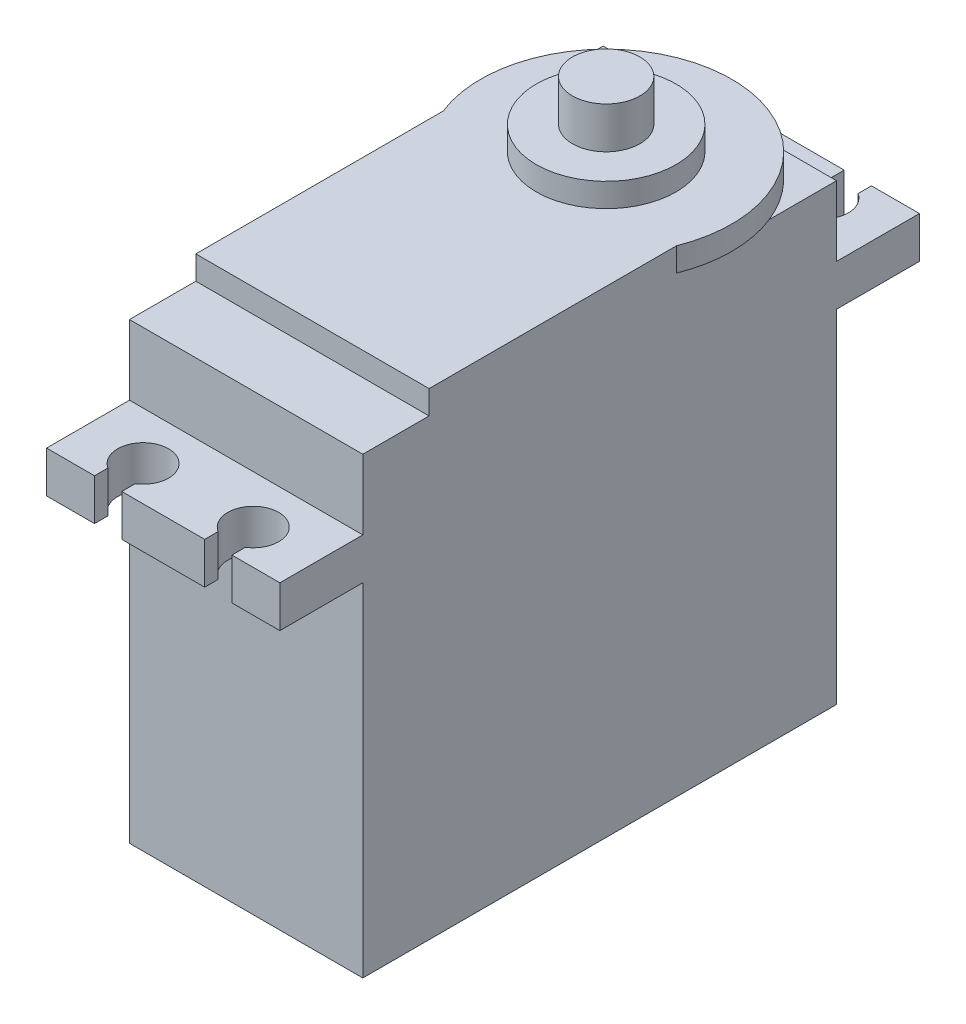
SolidWorks part; units mm, degrees
material "Nailon 101"
ref_plane "Front" through (0, 0, 0) normal (0, 0, 1) x (1, 0, 0)
ref_plane "Top" through (0, 0, 0) normal (0, 1, 0) x (1, 0, 0)
ref_plane "Right" through (0, 0, 0) normal (1, 0, 0) x (0, 0, -1)
sketch "Croquis1" plane through (0, 0, 0) normal (1, 0, 0) x (0, 0, -1)
  line L1 (0, 0) -> (40, 0)
  line L2 (0, 0) -> (0, 38.3)
  line L3 (0, 38.3) -> (40, 38.3)
  line L4 (40, 0) -> (40, 38.3)
  dimension "D1" = 40
  dimension "D2" = 38.3
extrude "Saliente-Extruir1" add sketch "Croquis1" along normal blind 19.7
sketch "Croquis2" plane through (0, 38.3, 0) normal (0, 1, 0) x (1, 0, 0)
  line L0 (0, 40) -> (0, 0) construction
  line L1 (0, 5.6) -> (19.7, 5.6)
  line L2 (0, 5.6) -> (0, 26.4837)
  line L4 (19.7, 5.6) -> (19.7, 26.4837)
  line L6 (19.7, 0) -> (0, 0) construction
  arc A0 (19.7, 26.4837) -> (0, 26.4837) centre (9.85, 30.4) ccw
  point P8 (9.85, 5.6)
  dimension "D3" = 21.2
  dimension "D1" = 5.6
  dimension "D2" = 9.85
  dimension "D4" = 9.85
  dimension "D5" = 26.4837
extrude "Saliente-Extruir2" add sketch "Croquis2" along normal blind 2
sketch "Croquis3" plane through (0, 40.3, 0) normal (0, 1, 0) x (1, 0, 0)
  circle A0 centre (9.85, 30.4) radius 5.9
  arc A1 (19.7, 26.4837) -> (0, 26.4837) centre (9.85, 30.4) ccw construction
  dimension "D1" = 11.8
extrude "Saliente-Extruir3" add sketch "Croquis3" along normal blind 2
sketch "Croquis4" plane through (0, 42.3, 0) normal (0, 1, 0) x (1, 0, 0)
  circle A0 centre (9.85, 30.4) radius 2.85
  circle A1 centre (9.85, 30.4) radius 5.9 construction
  dimension "D1" = 5.7
extrude "Saliente-Extruir4" add sketch "Croquis4" along normal blind 3.5
chamfer "Chaflán1" [suppressed] distance 1 angle 25
ref_plane "Plano1" through (0, 32.4, 0) normal (0, 1, 0) x (1, 0, 0)
sketch "Croquis5" plane through (0, 32.4, 0) normal (0, 1, 0) x (1, 0, 0)
  line L0 (19.7, 5.6) -> (19.7, 26.4837) construction
  line L1 (0, 0) -> (19.7, 0)
  line L2 (0, 0) -> (0, -7)
  line L3 (0, -7) -> (4.05, -7)
  line L4 (19.7, 0) -> (19.7, -7)
  line L5 (5.2, -1.9) -> (5.2, 0) construction
  line L6 (0, 40) -> (19.7, 40)
  line L7 (0, 40) -> (0, 47)
  line L8 (0, 47) -> (4.05, 47)
  line L9 (19.7, 40) -> (19.7, 47)
  line L10 (9.85, 47) -> (9.85, 22.3791) construction
  line L11 (5.2, 44.05) -> (5.2, 48.783) construction
  line L13 (4.05, 47) -> (4.05, 45.8666)
  line L15 (6.35, 47) -> (6.35, 45.8666)
  line L16 (5.2, -4.05) -> (5.2, -8.9222) construction
  line L18 (4.05, -7) -> (4.05, -5.8666)
  line L20 (6.35, -7) -> (6.35, -5.8666)
  line L21 (6.35, -7) -> (13.35, -7)
  line L22 (6.35, 47) -> (13.35, 47)
  line L23 (15.65, -7) -> (15.65, -5.8666)
  line L24 (13.35, -7) -> (13.35, -5.8666)
  line L25 (15.65, 47) -> (15.65, 45.8666)
  line L26 (13.35, 47) -> (13.35, 45.8666)
  line L27 (15.65, 47) -> (19.7, 47)
  line L28 (15.65, -7) -> (19.7, -7)
  arc A0 (4.05, 45.8666) -> (6.35, 45.8666) centre (5.2, 44.05) ccw
  arc A1 (6.35, -5.8666) -> (4.05, -5.8666) centre (5.2, -4.05) ccw
  arc A2 (13.35, -5.8666) -> (15.65, -5.8666) centre (14.5, -4.05) cw
  arc A3 (15.65, 45.8666) -> (13.35, 45.8666) centre (14.5, 44.05) cw
  dimension "D2" = 4.3
  dimension "D4" = 5.2
  dimension "D5" = 4.05
  dimension "D1" = 7
  dimension "D3" = 1.9
extrude "Saliente-Extruir5" add sketch "Croquis5" against normal blind 3.5
